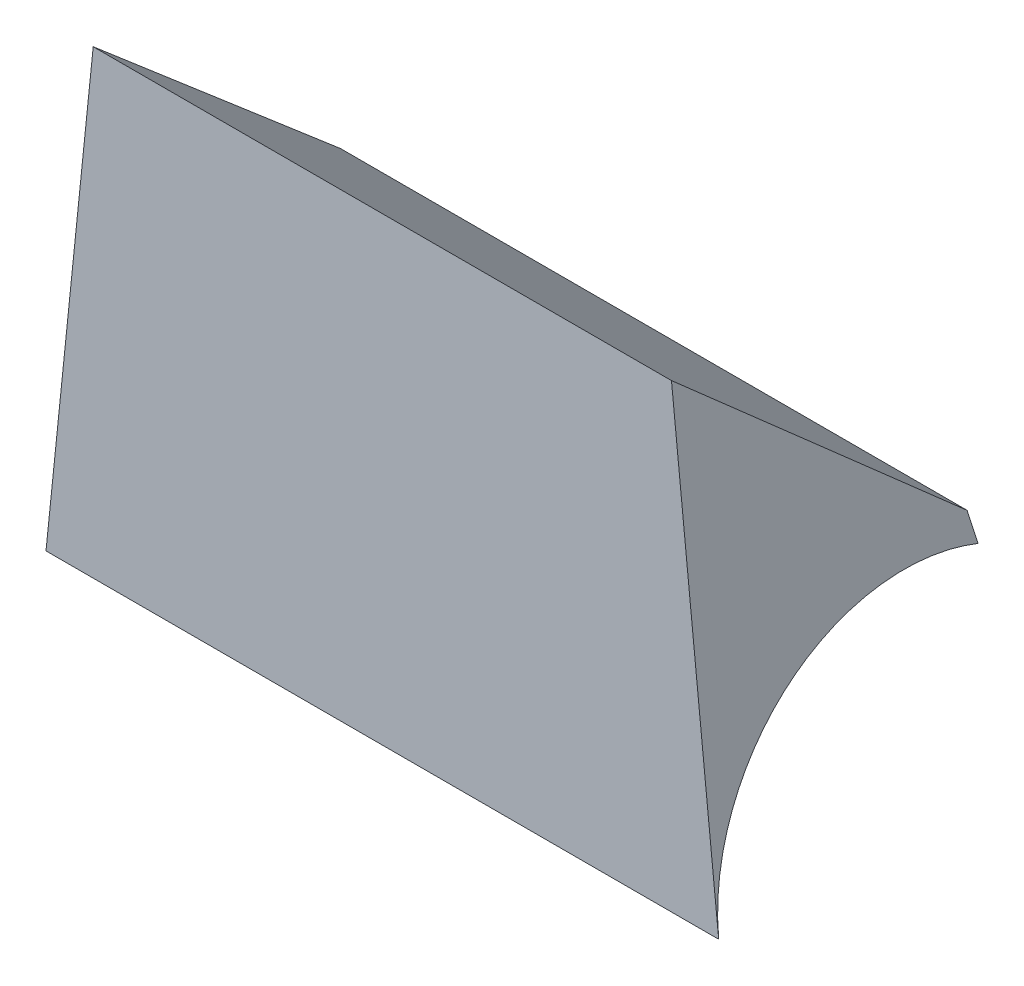
SolidWorks part; units mm, degrees
material "3.3320 (EN-AW 5019)"
ref_plane "Спереди" through (0, 0, 0) normal (0, 0, 1) x (1, 0, 0)
ref_plane "Сверху" through (0, 0, 0) normal (0, 1, 0) x (1, 0, 0)
ref_plane "Справа" through (0, 0, 0) normal (1, 0, 0) x (0, 0, -1)
sketch "Эскиз1" plane through (0, 0, 0) normal (1, 0, 0) x (0, 0, -1)
  line L0 (0, 0) -> (0, -39)
  line L1 (0, 0) -> (23, -19.9936)
  line L2 (23, -19.9936) -> (23.6543, -22.6179)
  line L3 (0, 0) -> (102.7314, 0) construction
  arc A0 (23.6543, -22.6179) -> (0, -39) centre (17.5, -39) ccw
  point P3 (17.5, -39)
  dimension "D1" = 39
  dimension "D2" = 23
  dimension "D4" = 41
  dimension "D5" = 35
  dimension "D6" = 17.5
  dimension "D7" = 39
extrude "Бобышка-Вытянуть1" add sketch "Эскиз1" along normal blind 57 contours L1 L2 A0 L0
sketch "Эскиз2" plane through (0, 0, 0) normal (0, 0, 1) x (1, 0, 0)
  line L0 (57, 0) -> (0, 0) construction
  line L1 (67.9966, 0) -> (53, 0)
  line L2 (67.9966, 0) -> (67.9966, -39)
  line L3 (67.9966, -39) -> (57, -39)
  line L4 (53, 0) -> (57, -39)
  line L5 (0, -39) -> (-10.9966, -39)
  line L6 (0, -39) -> (4, 0)
  line L7 (4, 0) -> (-10.9966, 0)
  line L8 (-10.9966, -39) -> (-10.9966, 0)
  dimension "D1" = 49
extrude "Вырез-Вытянуть1" cut sketch "Эскиз2" against normal through all
ref_plane "Средняя плоскость" through (28.5, 0, 0) normal (1, 0, 0) x (0, 0, -1)
